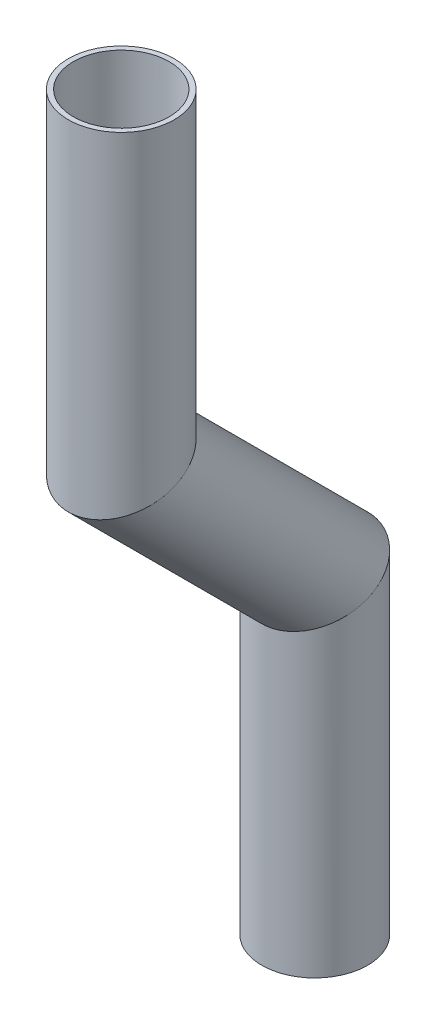
SolidWorks part; units mm, degrees
ref_plane "Front Plane" through (0, 0, 0) normal (0, 0, 1) x (1, 0, 0)
ref_plane "Top Plane" through (0, 0, 0) normal (0, 1, 0) x (1, 0, 0)
ref_plane "Right Plane" through (0, 0, 0) normal (1, 0, 0) x (0, 0, -1)
sketch "Sketch1" plane through (0, 0, 0) normal (1, 0, 0) x (0, 0, -1)
  line L0 (-302.5722, -54.9174) -> (-302.5722, -93.0174)
  line L1 (-302.5722, -93.0174) -> (-279.3723, -116.2172)
  line L2 (-279.3723, -116.2172) -> (-279.3723, -154.3172)
  line L3 (-302.5722, -93.0174) -> (-302.5722, -130.7988) construction
  point P2 (0, 0)
  point P6 (-302.5722, -93.0174)
  dimension "D1" = 45
  dimension "D2" = 38.1
  dimension "D3" = 38.1
other "Pipe 0.5 SCH 40(1)"
ref_plane "Plane1" through (0, -54.9174, 302.5722) normal (0, -1, 0) x (0, 0, -1)
sketch "Sketch11" plane through (0, -54.9174, 302.5722) normal (0, -1, 0) x (0, 0, -1)
  circle A0 centre (0, 0) radius 5.7404
  circle A1 centre (0, 0) radius 6.35
  point P5 (0, 0)
  dimension "In_dia" = 11.4808
  dimension "Out_dia" = 12.7
